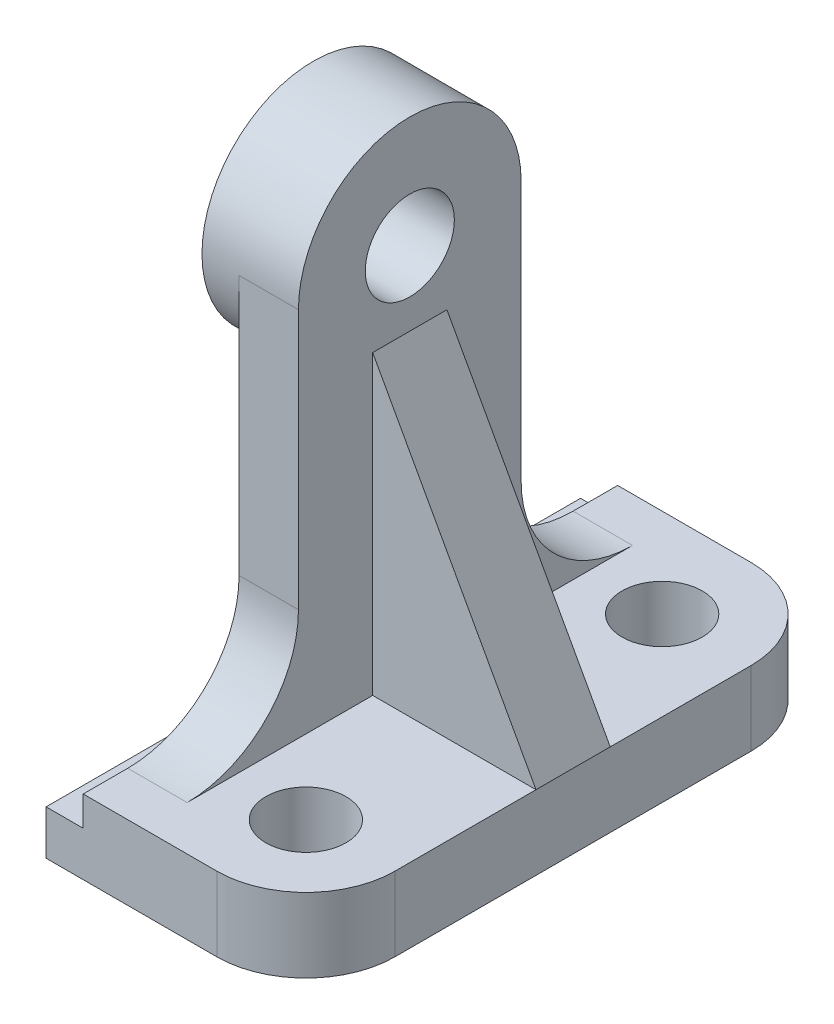
SolidWorks part; units mm, degrees
ref_plane "Front Plane" through (0, 0, 0) normal (0, 0, 1) x (1, 0, 0)
ref_plane "Top Plane" through (0, 0, 0) normal (0, 1, 0) x (1, 0, 0)
ref_plane "Right Plane" through (0, 0, 0) normal (1, 0, 0) x (0, 0, -1)
sketch "Sketch1" plane through (0, 0, 0) normal (0, 0, 1) x (1, 0, 0)
  line L0 (0, 0) -> (0, 6)
  line L1 (0, 6) -> (5, 6)
  line L2 (5, 6) -> (5, 10)
  line L3 (5, 10) -> (35, 10)
  line L4 (35, 10) -> (35, 0)
  line L5 (35, 0) -> (0, 0)
  dimension "D1" = 35
  dimension "D2" = 10
  dimension "D3" = 4
  dimension "D4" = 5
extrude "Boss-Extrude1" add sketch "Sketch1" along normal mid plane 72
fillet "Fillet1" radius 12 2 edges at (35, 5, -36) (35, 5, 36)
sketch "Sketch2" plane through (5, 0, 0) normal (-1, 0, 0) x (0, 0, 1)
  line L0 (-15, 60) -> (-15, 10)
  line L1 (36, 10) -> (-36, 10) construction
  line L2 (-15, 10) -> (15, 10)
  line L3 (15, 10) -> (15, 60)
  arc A0 (15, 60) -> (-15, 60) centre (0, 60) ccw
  dimension "D1" = 30
  dimension "D2" = 60
extrude "Boss-Extrude2" add sketch "Sketch2" against normal blind 8
fillet "Fillet2" radius 15 2 edges at (9, 10, -15) (9, 10, 15)
sketch "Sketch3" plane through (5, 0, 0) normal (-1, 0, 0) x (0, 0, 1)
  circle A0 centre (0, 60) radius 15
  arc A1 (15, 60) -> (-15, 60) centre (0, 60) ccw construction
extrude "Boss-Extrude3" add sketch "Sketch3" along normal blind 5
hole_wizard "Hole1" positions "Sketch5" profile "Sketch6" legacy end condition up to next
sketch "Sketch5" plane through (13, 0, 0) normal (1, 0, 0) x (0, 0, -1)
  point P0 (0, 60)
sketch "Sketch6" plane through (13, 60, 0) normal (0, 1, 0) x (0, 0, -1)
  line L0 (0, 0) -> (0, 13)
  line L1 (0, 13) -> (6, 13)
  line L2 (6, 13) -> (6, 0)
  line L3 (6, 0) -> (0, 0)
  line L4 (0, 110) -> (0, -10) construction
  dimension "Diameter" = 12
  dimension "Depth" = 13
hole_wizard "M12x1.25 Tapped Hole1" positions "Sketch7" profile "Sketch8" tap size "M12x1.25" standard "ANSI Metric" end condition up to next
sketch "Sketch7" plane through (0, 10, 0) normal (0, 1, 0) x (1, 0, 0)
  point P0 (23, -24)
  point P3 (23, 24)
sketch "Sketch8" plane through (23, 10, 24) normal (1, 0, 0) x (0, 0, 1)
  line L0 (0, 0) -> (0, 10)
  line L1 (0, 10) -> (5.4, 10)
  line L2 (5.4, 10) -> (5.4, 0)
  line L5 (5.4, 0) -> (0, 0)
  line L11 (0, -6.35) -> (0, 107.95) construction
  dimension "Thru Tap Drill Dia." = 10.8
  dimension "Thru Tap Drill Depth" = 10
cosmetic thread "Hole Thread1" parameters "D2"=12
cosmetic thread "Hole Thread2" parameters "D2"=12
sketch "Sketch9" plane through (0, 0, 0) normal (0, 0, 1) x (1, 0, 0)
  line L0 (13, 50) -> (35, 10)
  line L1 (13, 25) -> (13, 60) construction
  line L2 (35, 10) -> (23, 10) construction
  dimension "D1" = 40
rib "Rib1" sketch "Sketch9" sketch "Sketch9" thickness 10 extrusion direction parallel to sketch draft on no parameters "D1"=10
